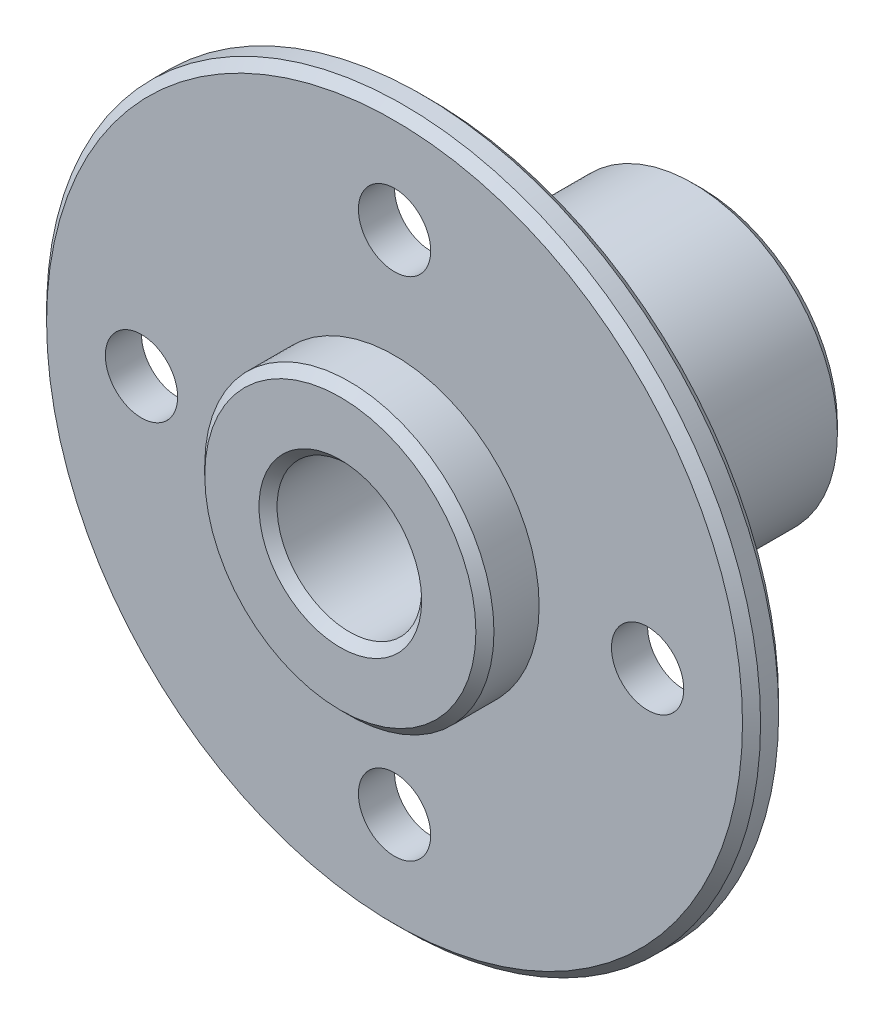
SolidWorks part; units mm, degrees
ref_plane "前视基准面" through (0, 0, 0) normal (0, 0, 1) x (1, 0, 0)
ref_plane "上视基准面" through (0, 0, 0) normal (0, 1, 0) x (1, 0, 0)
ref_plane "右视基准面" through (0, 0, 0) normal (1, 0, 0) x (0, 0, -1)
sketch "草图1" plane through (0, 0, 0) normal (0, 0, 1) x (1, 0, 0)
  circle A0 centre (0, 0) radius 19.75
  dimension "D1" = 39.5
extrude "凸台-拉伸1" add sketch "草图1" along normal blind 2
sketch "草图2" plane through (0, 0, 2) normal (0, 0, 1) x (1, 0, 0)
  circle A0 centre (0, 0) radius 8
  dimension "D1" = 16
extrude "凸台-拉伸2" add sketch "草图2" along normal blind 3
sketch "草图3" plane through (0, 0, 0) normal (0, 0, -1) x (-1, 0, 0)
  circle A0 centre (0, 0) radius 8
  dimension "D1" = 16
extrude "凸台-拉伸3" add sketch "草图3" along normal blind 15
hole_wizard "M8 螺纹孔1" positions "草图5" profile "草图4" tap size "M8" standard "GB" end condition up to next
sketch "草图5" plane through (0, 0, 5) normal (0, 0, 1) x (1, 0, 0)
  point P0 (0, 0)
sketch "草图4" plane through (0, 0, 5) normal (1, 0, 0) x (0, -1, 0)
  line L0 (0, 0) -> (0, 20)
  line L1 (0, 20) -> (4, 20)
  line L2 (4, 20) -> (4, 0)
  line L5 (4, 0) -> (0, 0)
  line L11 (0, -6.35) -> (0, 107.95) construction
  dimension "螺纹线主直径" = 8
  dimension "通孔螺纹孔钻头深度" = 20
hole_wizard "M4 螺纹孔1" positions "草图7" profile "草图6" tap size "M4" standard "GB" end condition up to next
sketch "草图7" plane through (0, 0, 2) normal (0, 0, 1) x (1, 0, 0)
  line L0 (0, 0) -> (0, 23.029) construction
  line L2 (0, 0) -> (0, -23.241) construction
  line L5 (-23.9824, 0) -> (0, 0) construction
  line L7 (0, 0) -> (25.8377, 0) construction
  circle A0 centre (0, 0) radius 14 construction
  point P0 (0, 14)
  point P1 (0, -14)
  point P3 (-14, 0)
  point P5 (14, 0)
  dimension "D1" = 28
sketch "草图6" plane through (0, 14, 2) normal (1, 0, 0) x (0, -1, 0)
  line L0 (0, 0) -> (0, 2)
  line L1 (0, 2) -> (2, 2)
  line L2 (2, 2) -> (2, 0)
  line L5 (2, 0) -> (0, 0)
  line L11 (0, -6.35) -> (0, 107.95) construction
  dimension "螺纹线主直径" = 4
  dimension "通孔螺纹孔钻头深度" = 2
chamfer "倒角1" distance 0.5 angle 45 6 edges at (-4, 0, -15) (-8, 0, -15) (19.75, 0, 0) (19.75, 0, 2) (4, 0, 5) (8, 0, 5)
